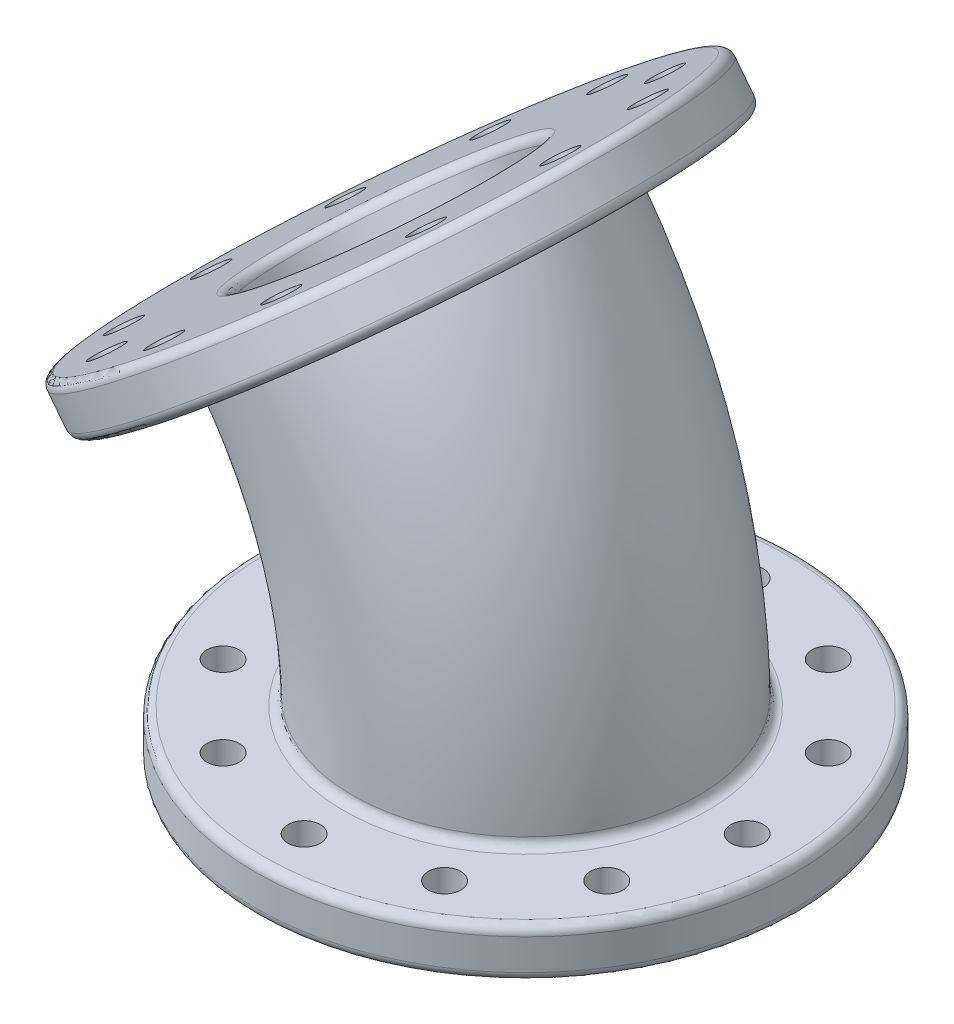
SolidWorks part; units mm, degrees
material "AISI 304"
ref_plane "Front Plane" through (0, 0, 0) normal (0, 0, 1) x (1, 0, 0)
ref_plane "Top Plane" through (0, 0, 0) normal (0, 1, 0) x (1, 0, 0)
ref_plane "Right Plane" through (0, 0, 0) normal (1, 0, 0) x (0, 0, -1)
sketch "Sketch1" plane through (0, 0, 0) normal (0, 1, 0) x (1, 0, 0)
  circle A0 centre (0, 0) radius 61
  circle A1 centre (0, 0) radius 28
  circle A2 centre (0, 0) radius 50 construction
  circle A3 centre (0, 50) radius 3.665
  circle A4 centre (25, 43.3013) radius 3.665
  circle A5 centre (43.3013, 25) radius 3.665
  circle A6 centre (50, 0) radius 3.665
  circle A7 centre (43.3013, -25) radius 3.665
  circle A8 centre (25, -43.3013) radius 3.665
  circle A9 centre (0, -50) radius 3.665
  circle A10 centre (-25, -43.3013) radius 3.665
  circle A11 centre (-43.3013, -25) radius 3.665
  circle A12 centre (-50, 0) radius 3.665
  circle A13 centre (-43.3013, 25) radius 3.665
  circle A14 centre (-25, 43.3013) radius 3.665
  point P32 (0, 0)
  dimension "D1" = 56
  dimension "D4" = 7.33
  dimension "D2" = 33
  dimension "D3" = 11
  dimension "D5" = 12
extrude "Boss-Extrude1" add sketch "Sketch1" along normal blind 11
sketch "Sketch2" plane through (0, 11, 0) normal (0, 1, 0) x (1, 0, 0)
  line L0 (-117, 31.3779) -> (-117, -30.405) construction
  circle A0 centre (0, 0) radius 39
  circle A1 centre (0, 0) radius 28
  circle A2 centre (0, 0) radius 28 construction
  point P8 (-39, 0)
  dimension "D1" = 11
  dimension "D2" = 78
revolve "Revolve1" add sketch "Sketch2" angle 38 about L0
sketch "Sketch3" plane through (-49.6842, 63.5929, 0) normal (-0.6157, 0.788, 0) x (0.788, 0.6157, 0)
  circle A0 centre (31.575, 0) radius 28
  circle A1 centre (31.575, 0) radius 61
  circle A2 centre (31.575, 0) radius 50 construction
  circle A3 centre (31.575, 50) radius 3.6667
  circle A4 centre (31.575, 0) radius 28 construction
  circle A5 centre (56.575, 43.3013) radius 3.6667
  circle A6 centre (74.8763, 25) radius 3.6667
  circle A7 centre (81.575, 0) radius 3.6667
  circle A8 centre (74.8763, -25) radius 3.6667
  circle A9 centre (56.575, -43.3013) radius 3.6667
  circle A10 centre (31.575, -50) radius 3.6667
  circle A11 centre (6.575, -43.3013) radius 3.6667
  circle A12 centre (-11.7263, -25) radius 3.6667
  circle A13 centre (-18.425, 0) radius 3.6667
  circle A14 centre (-11.7263, 25) radius 3.6667
  circle A15 centre (6.575, 43.3013) radius 3.6667
  point P32 (31.575, 0)
  dimension "D3" = 7.3333
  dimension "D1" = 33
  dimension "D2" = 11
  dimension "D4" = 12
extrude "Boss-Extrude2" add sketch "Sketch3" along normal blind 11
fillet "Fillet1" radius 2 8 edges at (0, 0, 61) (0, 11, 61) (-72.8714, 45.477, 0) (-79.6437, 54.1452, 0) (0, 0, 28) (-53.6393, 74.462, 0) (0, 11, 39) (-24.8027, 83.0324, 39)
equation "\"A\"=56"
equation "\"D1@Sketch1\"=\"A\""
equation "\"B\"=11"
equation "\"D2@Sketch1\"=\"B\"*3"
equation "\"D3@Sketch1\"=\"B\""
equation "\"D1@Boss-Extrude1\"=\"B\""
equation "\"D1@Sketch2\"=\"B\""
equation "\"C\"=38"
equation "\"D1@Revolve1\"=\"C\""
equation "\"D1@Sketch3\"=\"B\"*3"
equation "\"D2@Sketch3\"=\"B\""
equation "\"D3@Sketch3\"=\"B\"*2/3"
equation "\"D1@Boss-Extrude2\"=\"B\""
